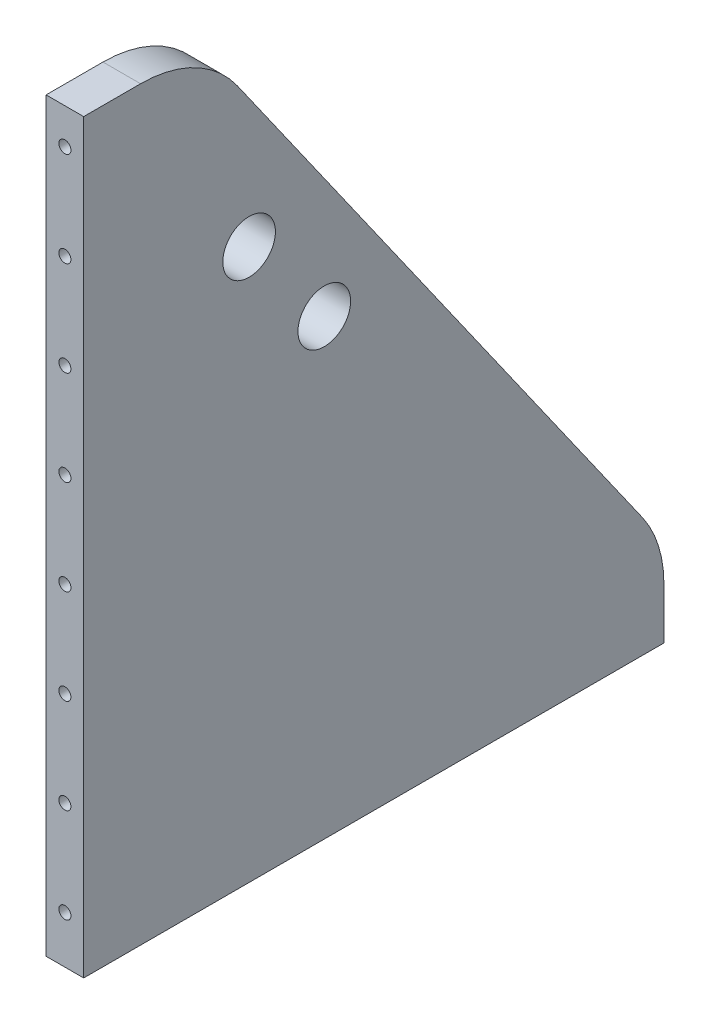
SolidWorks part; units mm, degrees
material "Low Carbon Steel"
ref_plane "Front Plane" through (0, 0, 0) normal (0, 0, 1) x (1, 0, 0)
ref_plane "Top Plane" through (0, 0, 0) normal (0, 1, 0) x (1, 0, 0)
ref_plane "Right Plane" through (0, 0, 0) normal (1, 0, 0) x (0, 0, -1)
sketch "Sketch1" plane through (0, 0, 0) normal (1, 0, 0) x (0, 0, -1)
  line L0 (0, 0) -> (0, 640)
  line L1 (0, 640) -> (58.0495, 640)
  line L2 (139.8687, 597.4946) -> (481.8192, 110.8727)
  line L3 (500, 53.3782) -> (500, 0)
  line L4 (500, 0) -> (0, 0)
  arc A0 (481.8192, 110.8727) -> (500, 53.3782) centre (400, 53.3782) cw
  arc A1 (58.0495, 640) -> (139.8687, 597.4946) centre (58.0495, 540) cw
  point P8 (500, 85)
  point P11 (110, 640)
  dimension "D5" = 100
  dimension "D1" = 500
  dimension "D2" = 640
  dimension "D3" = 110
  dimension "D4" = 85
extrude "Boss-Extrude1" add sketch "Sketch1" along normal blind 31.75
sketch "Sketch2" plane through (0, 0, 0) normal (-1, 0, 0) x (0, 0, 1)
  line L0 (0, 640) -> (-10, 640)
  line L1 (-58.0495, 640) -> (0, 640) construction
  line L2 (-10, 640) -> (-10, 10)
  line L3 (-10, 10) -> (-500, 10)
  line L4 (-500, 0) -> (-500, 53.3782) construction
  line L5 (-500, 10) -> (-500, 0)
  line L6 (-500, 0) -> (0, 0)
  line L7 (0, 0) -> (0, 640)
  dimension "D1" = 10
  dimension "D2" = 10
extrude "Cut-Extrude1" cut sketch "Sketch2" against normal through all
hole_wizard "M12 Tapped Hole1" positions "Sketch3" profile "Sketch4" tap size "M12" standard "Peddi DIN"
sketch "Sketch3" plane through (0, 0, -10) normal (0, 0, 1) x (1, 0, 0)
  line L0 (15.875, 50) -> (15.875, 10) construction
  line L1 (31.75, 10) -> (0, 10) construction
  point P0 (15.875, 50)
  dimension "D1" = 40
sketch "Sketch4" plane through (15.875, 50, -10) normal (1, 0, 0) x (0, -1, 0)
  line L0 (0, 0) -> (0, 47.0544)
  line L1 (0, 47.0544) -> (5.1, 43.99)
  line L2 (5.1, 43.99) -> (5.1, 0)
  line L5 (5.1, 0) -> (0, 0)
  line L10 (0, 47.0544) -> (-5.1, 43.99) construction
  line L11 (0, -6.35) -> (0, 107.95) construction
  dimension "Tap Drill Dia." = 10.2
  dimension "Tap Drill Depth" = 43.99
  dimension "Drill Angle" = 118
cosmetic thread "Hole Thread1" parameters "D1"=30, "D2"=12
pattern_linear "LPattern1" count 8 spacing 80 along (0, 1, 0) of "M12 Tapped Hole1"
hole_wizard "M12 Tapped Hole2" positions "Sketch5" profile "Sketch6" tap size "M12" standard "Peddi DIN"
sketch "Sketch5" plane through (0, 10, 0) normal (0, -1, 0) x (-1, 0, 0)
  line L0 (-15.875, 10) -> (-15.875, 70) construction
  line L1 (-31.75, 10) -> (0, 10) construction
  point P0 (-15.875, 70)
  dimension "D1" = 60
sketch "Sketch6" plane through (15.875, 10, -70) normal (1, 0, 0) x (0, 0, -1)
  line L0 (0, 0) -> (0, 47.0544)
  line L1 (0, 47.0544) -> (5.1, 43.99)
  line L2 (5.1, 43.99) -> (5.1, 0)
  line L5 (5.1, 0) -> (0, 0)
  line L10 (0, 47.0544) -> (-5.1, 43.99) construction
  line L11 (0, -6.35) -> (0, 107.95) construction
  dimension "Tap Drill Dia." = 10.2
  dimension "Tap Drill Depth" = 43.99
  dimension "Drill Angle" = 118
cosmetic thread "Hole Thread2" parameters "D1"=30, "D2"=12
pattern_linear "LPattern2" count 6 spacing 80 along (0, 0, -1) of "M12 Tapped Hole2"
sketch "Sketch8" plane through (0, 0, 0) normal (-1, 0, 0) x (0, 0, 1)
  line L0 (-58.0495, 640) -> (-10, 640) construction
  line L1 (-10, 640) -> (-10, 10) construction
  line L3 (-481.8192, 110.8727) -> (-139.8687, 597.4946) construction
  circle A0 centre (-213.2, 392.35) radius 22.225
  circle A1 centre (-149.7, 474.9) radius 22.225
  dimension "D1" = 44.45
  dimension "D3" = 203.2
  dimension "D4" = 35.7229
  dimension "D5" = 139.7
  dimension "D6" = 165.1
  dimension "D2" = 247.65
  dimension "D7" = 40.2163
extrude "Cut-Extrude2" cut sketch "Sketch8" against normal through all
other "Freeze***"
